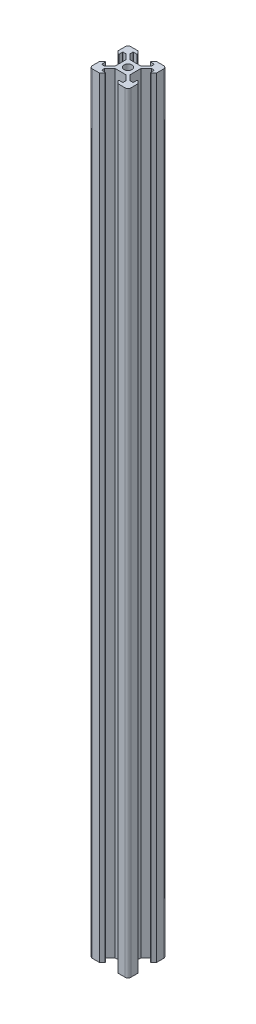
SolidWorks part; units mm, degrees
ref_plane "Alzado" through (0, 0, 0) normal (0, 0, 1) x (1, 0, 0)
ref_plane "Planta" through (0, 0, 0) normal (0, 1, 0) x (1, 0, 0)
ref_plane "Vista lateral" through (0, 0, 0) normal (1, 0, 0) x (0, 0, -1)
sketch "Croquis1" plane through (0, 0, 0) normal (0, 1, 0) x (1, 0, 0)
  line L0 (0, 0) -> (0, 10) construction
  line L1 (-10, 10) -> (10, 10)
  line L2 (-10, 10) -> (-10, -10)
  line L3 (-10, -10) -> (10, -10)
  line L4 (10, 10) -> (10, -10)
  line L5 (-10, 10) -> (10, -10) construction
  line L6 (-10, -10) -> (10, 10) construction
  line L7 (-4.9, 10) -> (-3.1, 8.2)
  line L8 (-3.1, 8.2) -> (-5.5393, 8.2)
  line L9 (-5.5393, 8.2) -> (-5.5393, 6.6)
  line L10 (-5.5393, 6.6) -> (-0.8567, 1.9173)
  line L11 (5.5393, 6.6) -> (0.8567, 1.9173)
  line L12 (5.5393, 8.2) -> (5.5393, 6.6)
  line L13 (3.1, 8.2) -> (5.5393, 8.2)
  line L14 (4.9, 10) -> (3.1, 8.2)
  line L15 (10, 4.9) -> (8.2, 3.1)
  line L16 (8.2, 3.1) -> (8.2, 5.5393)
  line L17 (8.2, 5.5393) -> (6.6, 5.5393)
  line L18 (6.6, 5.5393) -> (1.9173, 0.8567)
  line L19 (6.6, -5.5393) -> (1.9173, -0.8567)
  line L20 (8.2, -5.5393) -> (6.6, -5.5393)
  line L21 (8.2, -3.1) -> (8.2, -5.5393)
  line L22 (10, -4.9) -> (8.2, -3.1)
  line L23 (4.9, -10) -> (3.1, -8.2)
  line L24 (3.1, -8.2) -> (5.5393, -8.2)
  line L25 (5.5393, -8.2) -> (5.5393, -6.6)
  line L26 (5.5393, -6.6) -> (0.8567, -1.9173)
  line L27 (-5.5393, -6.6) -> (-0.8567, -1.9173)
  line L28 (-5.5393, -8.2) -> (-5.5393, -6.6)
  line L29 (-3.1, -8.2) -> (-5.5393, -8.2)
  line L30 (-4.9, -10) -> (-3.1, -8.2)
  line L31 (-10, -4.9) -> (-8.2, -3.1)
  line L32 (-8.2, -3.1) -> (-8.2, -5.5393)
  line L33 (-8.2, -5.5393) -> (-6.6, -5.5393)
  line L34 (-6.6, -5.5393) -> (-1.9173, -0.8567)
  line L35 (-6.6, 5.5393) -> (-1.9173, 0.8567)
  line L36 (-8.2, 5.5393) -> (-6.6, 5.5393)
  line L37 (-8.2, 3.1) -> (-8.2, 5.5393)
  line L38 (-10, 4.9) -> (-8.2, 3.1)
  line L39 (-3.9007, 2.84) -> (-3.9007, -2.84)
  line L40 (2.84, 3.9007) -> (-2.84, 3.9007)
  line L41 (3.9007, -2.84) -> (3.9007, 2.84)
  line L42 (-2.84, -3.9007) -> (2.84, -3.9007)
  circle A0 centre (0, 0) radius 2.1
  point P51 (0, 0)
  point P60 (0, 0)
  dimension "D1" = 4.2
  dimension "D2" = 20
  dimension "D3" = 45
  dimension "D4" = 1.6
  dimension "D5" = 0.75
  dimension "D6" = 1.8
  dimension "D7" = 3.1
  dimension "D9" = 5.68
  dimension "D8" = 4
  dimension "D10" = 4
extrude "Saliente-Extruir1" add sketch "Croquis1" along normal blind 400 contours A0 L10 L9 L8 L7 L1 L2 L38 L37 L36 L35 | A0 L34 L33 L32 L31 L2 L3 L30 L29 L28 L27 | A0 L26 L25 L24 L23 L3 L4 L22 L21 L20 L19 | A0 L18 L17 L16 L15 L4 L1 L14 L13 L12 L11 | A0 L35 L39 L34 | A0 L27 L42 L26 | A0 L19 L41 L18 | A0 L11 L40 L10
fillet "Redondeo1" radius 1.5 4 edges at (10, 200, 10) (-10, 200, 10) (-10, 200, -10) (10, 200, -10)
fillet "Redondeo2" radius 0.2 16 edges at (-5.5393, 200, 8.2) (5.5393, 200, 8.2) (8.2, 200, 5.5393) (8.2, 200, -5.5393) (5.5393, 200, -8.2) (-5.5393, 200, -8.2) (-8.2, 200, -5.5393) (-8.2, 200, 5.5393) (3.1, 200, 8.2) (-3.1, 200, 8.2) (8.2, 200, 3.1) (8.2, 200, -3.1) (3.1, 200, -8.2) (-3.1, 200, -8.2) (-8.2, 200, -3.1) (-8.2, 200, 3.1)
